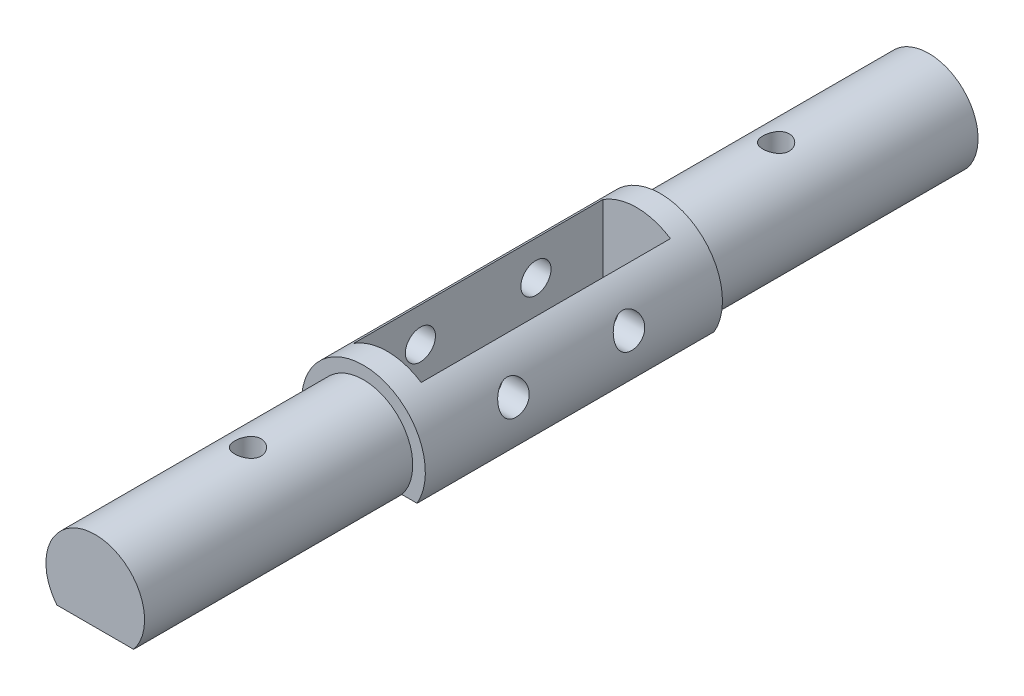
SolidWorks part; units mm, degrees
ref_plane "Front Plane" through (0, 0, 0) normal (0, 0, 1) x (1, 0, 0)
ref_plane "Top Plane" through (0, 0, 0) normal (0, 1, 0) x (1, 0, 0)
ref_plane "Right Plane" through (0, 0, 0) normal (1, 0, 0) x (0, 0, -1)
sketch "Sketch1" plane through (0, 0, 0) normal (0, 0, 1) x (1, 0, 0)
  line L0 (-6.4952, -3.75) -> (6.4952, -3.75)
  circle A0 centre (0, 0) radius 7.5
  dimension "D1" = 15
  dimension "D2" = 3.75
extrude "Boss-Extrude1" add sketch "Sketch1" along normal blind 101 contours L0 A0
sketch "Sketch3" plane through (0, 0, 101) normal (0, 0, 1) x (1, 0, 0)
  line L0 (-6.4952, -3.75) -> (6.4952, -3.75)
  circle A0 centre (0, 0) radius 5.975
  circle A1 centre (0, 0) radius 7.5
  line M3 (-6.4952, -3.75) -> (6.4952, -3.75)
  arc M4 (6.4952, -3.75) -> (-6.4952, -3.75) centre (0, 0) ccw
  dimension "D1" = 11.95
  dimension "D2" = 15
extrude "Cut-Extrude1" cut sketch "Sketch3" against normal blind 32.5 contours A0 M3 M4
sketch "Sketch4" plane through (0, 0, 0) normal (0, 0, -1) x (-1, 0, 0)
  line L0 (-6.4952, -3.75) -> (6.4952, -3.75)
  circle A0 centre (0, 0) radius 5.975
  circle A1 centre (0, 0) radius 7.5
  line M2 (-6.4952, -3.75) -> (6.4952, -3.75)
  arc M3 (6.4952, -3.75) -> (-6.4952, -3.75) centre (0, 0) ccw
  dimension "D1" = 11.95
  dimension "D2" = 15
extrude "Cut-Extrude2" cut sketch "Sketch4" against normal blind 32.5 contours A0 M2 M3
sketch "Sketch5" plane through (0, -3.75, 0) normal (0, -1, 0) x (1, 0, 0)
  line L0 (6.4952, 68.5) -> (6.4952, 32.5) construction
  line L1 (-6.4952, 32.5) -> (-6.4952, 68.5) construction
  line L2 (-6.4952, 50.5) -> (6.4952, 50.5) construction
  line L3 (0, 50.5) -> (0, 65.6) construction
  line L4 (0, 65.6) -> (-4.1, 65.6) construction
  line L5 (0, 50.5) -> (0, 35.4) construction
  line L6 (0, 35.4) -> (4.1, 35.4) construction
  line L8 (-4.1, 65.6) -> (4.1, 65.6)
  line L9 (-4.1, 65.6) -> (-4.1, 35.4)
  line L10 (-4.1, 35.4) -> (4.1, 35.4)
  line L11 (4.1, 65.6) -> (4.1, 35.4)
  point P8 (0, 50.5)
  dimension "D1" = 15.1
  dimension "D2" = 4.1
extrude "Cut-Extrude3" cut sketch "Sketch5" against normal through all both and the other way through all contours L11 L8 L9 L10
ref_plane "Plane5" through (-7.5, 0, 0) normal (-1, 0, 0) x (0, 0, 1)
sketch "Sketch10" plane through (-7.5, 0, 0) normal (-1, 0, 0) x (0, 0, 1)
  line L0 (32.5, 2.1127) -> (68.5, 2.1127) construction
  line L1 (68.5, -3.75) -> (68.5, 7.5) construction
  line L2 (32.5, 7.5) -> (32.5, -3.75) construction
  circle A0 centre (43.5, 2.1127) radius 1.825
  circle A1 centre (57.5, 2.1127) radius 1.825
  point P2 (57.5, 2.1127)
  point P5 (43.5, 2.1127)
  point P8 (50.5, 2.1127)
  dimension "D3" = 3.65
  dimension "D4" = 3.65
  dimension "D1" = 7
  dimension "D2" = 7
extrude "Cut-Extrude4" cut sketch "Sketch10" against normal through all both and the other way through all contours L0 A0 | A0 L0 | L0 A1 | A1 L0
sketch "Sketch11" plane through (0, -3.75, 0) normal (0, -1, 0) x (1, 0, 0)
  line L0 (0, 0) -> (0, 101) construction
  line L1 (-4.6517, 0) -> (4.6517, 0) construction
  line L2 (-4.6517, 101) -> (4.6517, 101) construction
  line L3 (-5.975, 32.5) -> (5.975, 32.5) construction
  line L4 (7.5, 68.5) -> (-7.5, 68.5) construction
  point P6 (0, 18.5)
  point P7 (0, 82.5)
  dimension "D1" = 14
  dimension "D2" = 14
hole_wizard "Hole1" positions "3DSketch1" profile "Sketch13" legacy end condition through all
sketch3d "3DSketch1"
  point P0 (0, -3.75, 82.5)
  point P3 (0, -3.75, 18.5)
sketch "Sketch13" plane through (0, -3.75, 82.5) normal (1, 0, 0) x (0, 0, -1)
  line L0 (0, 0) -> (0, 11.25)
  line L1 (0, 11.25) -> (1.6, 11.25)
  line L2 (1.6, 11.25) -> (1.6, 1.55)
  line L3 (1.6, 1.55) -> (3.15, 0)
  line L4 (3.15, 0) -> (0, 0)
  line L5 (0, -6.4453) -> (0, 115.525) construction
  line L6 (-1.6, 1.55) -> (-3.15, 0) construction
  dimension "Diameter" = 3.2
  dimension "Depth" = 11.25
  dimension "C-Sink Angle" = 90
  dimension "C-Sink Diameter" = 6.3
